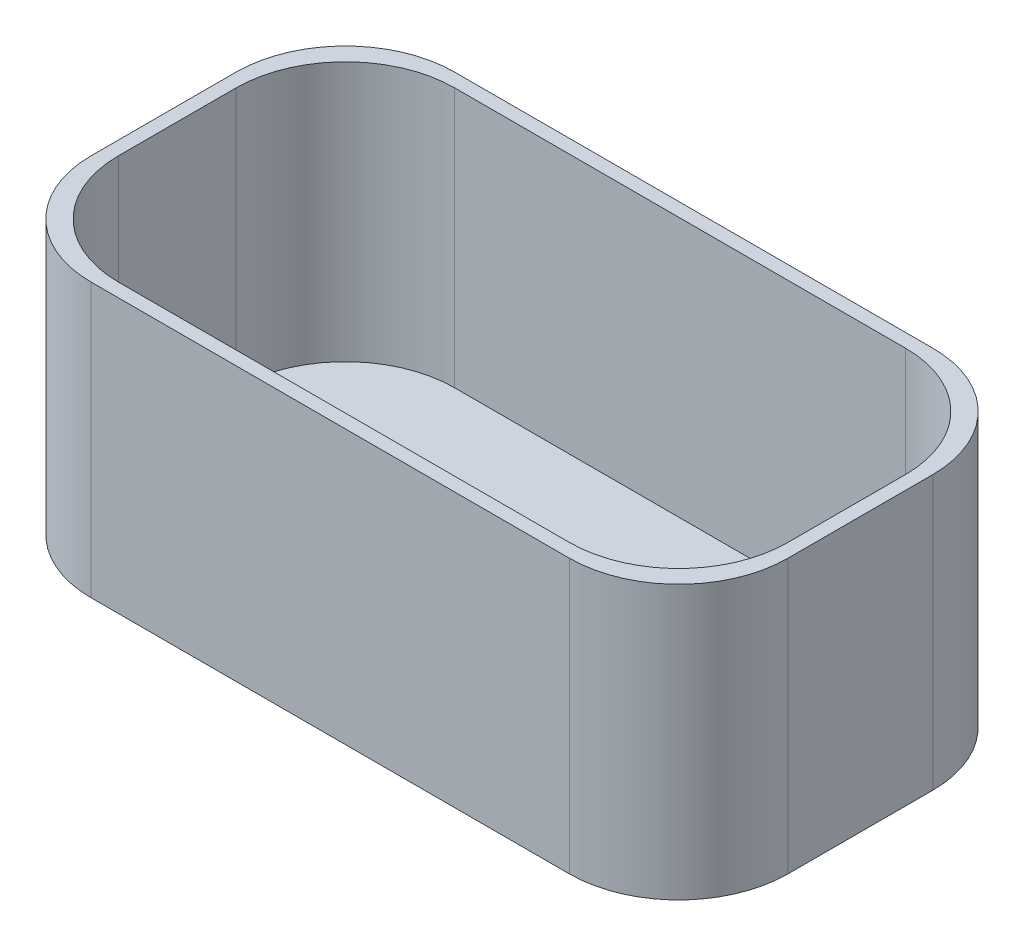
SolidWorks part; units mm, degrees
ref_plane "前视基准面" through (0, 0, 0) normal (0, 0, 1) x (1, 0, 0)
ref_plane "上视基准面" through (0, 0, 0) normal (0, 1, 0) x (1, 0, 0)
ref_plane "右视基准面" through (0, 0, 0) normal (1, 0, 0) x (0, 0, -1)
sketch "草图1" plane through (0, 0, 0) normal (0, 1, 0) x (1, 0, 0)
  line L1 (-127.45, 66.5) -> (127.45, 66.5)
  line L2 (-127.45, 66.5) -> (-127.45, -66.5)
  line L3 (-127.45, -66.5) -> (127.45, -66.5)
  line L4 (127.45, 66.5) -> (127.45, -66.5)
  line L5 (-127.45, 66.5) -> (127.45, -66.5) construction
  line L6 (-127.45, -66.5) -> (127.45, 66.5) construction
  point P0 (0, 0)
  dimension "D1" = 254.9
  dimension "D2" = 133
extrude "凸台-拉伸1" add sketch "草图1" along normal blind 100
shell "抽壳1" thickness 5
fillet "圆角1" radius 40 4 edges at (122.45, 52.5, 61.5) (122.45, 52.5, -61.5) (-122.45, 52.5, -61.5) (-122.45, 52.5, 61.5)
fillet "圆角2" radius 40 4 edges at (-127.45, 50, -66.5) (127.45, 50, -66.5) (127.45, 50, 66.5) (-127.45, 50, 66.5)
sketch "草图2" plane through (0, 5, 0) normal (0, 1, 0) x (1, 0, 0)
  line L0 (-25, 0) -> (25, 0) construction
  line L1 (-25, 17.5) -> (25, 17.5)
  line L2 (-25, -17.5) -> (25, -17.5)
  arc A0 (-25, 17.5) -> (-25, -17.5) centre (-25, 0) ccw
  arc A1 (25, -17.5) -> (25, 17.5) centre (25, 0) ccw
  point P3 (0, 0)
  point P8 (0, 0)
  dimension "D1" = 50
  dimension "D2" = 35
extrude "切除-拉伸1" cut sketch "草图2" against normal blind 100
sketch "草图3" plane through (0, 100, 0) normal (0, 1, 0) x (1, 0, 0)
  line L4 (87.45, 66.5) -> (-87.45, 66.5)
  line L5 (-127.45, 26.5) -> (-127.45, -26.5)
  line L6 (-87.45, -66.5) -> (87.45, -66.5)
  line L7 (127.45, -26.5) -> (127.45, 26.5)
  line L8 (87.45, 66.5) -> (-87.45, 66.5)
  line L9 (-127.45, 26.5) -> (-127.45, -26.5)
  line L10 (-87.45, -66.5) -> (87.45, -66.5)
  line L11 (127.45, -26.5) -> (127.45, 26.5)
  arc A4 (-87.45, 66.5) -> (-127.45, 26.5) centre (-87.45, 26.5) ccw
  arc A5 (-127.45, -26.5) -> (-87.45, -66.5) centre (-87.45, -26.5) ccw
  arc A6 (87.45, -66.5) -> (127.45, -26.5) centre (87.45, -26.5) ccw
  arc A7 (127.45, 26.5) -> (87.45, 66.5) centre (87.45, 26.5) ccw
  arc A8 (-87.45, 66.5) -> (-127.45, 26.5) centre (-87.45, 26.5) ccw
  arc A9 (-127.45, -26.5) -> (-87.45, -66.5) centre (-87.45, -26.5) ccw
  arc A10 (87.45, -66.5) -> (127.45, -26.5) centre (87.45, -26.5) ccw
  arc A11 (127.45, 26.5) -> (87.45, 66.5) centre (87.45, 26.5) ccw
  dimension "D1" = 0
